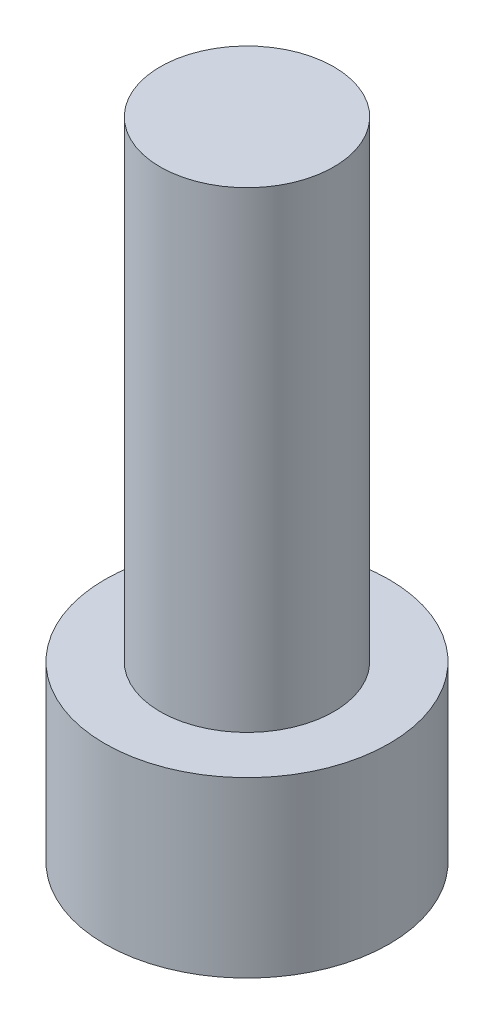
SolidWorks part; units mm, degrees
ref_plane "前视基准面" through (0, 0, 0) normal (0, 0, 1) x (1, 0, 0)
ref_plane "上视基准面" through (0, 0, 0) normal (0, 1, 0) x (1, 0, 0)
ref_plane "右视基准面" through (0, 0, 0) normal (1, 0, 0) x (0, 0, -1)
sketch "Sketch1" plane through (0, 0, 0) normal (0, 1, 0) x (1, 0, 0)
  circle A0 centre (0, 0) radius 2.8702
  dimension "D1" = 5.7404
extrude "Boss-Extrude1" add sketch "Sketch1" along normal blind 3.5052
sketch "Sketch2" plane through (0, 3.5052, 0) normal (0, 1, 0) x (1, 0, 0)
  circle A0 centre (0, 0) radius 1.7526
  dimension "D1" = 3.5052
extrude "Boss-Extrude2" add sketch "Sketch2" along normal blind 9.525
